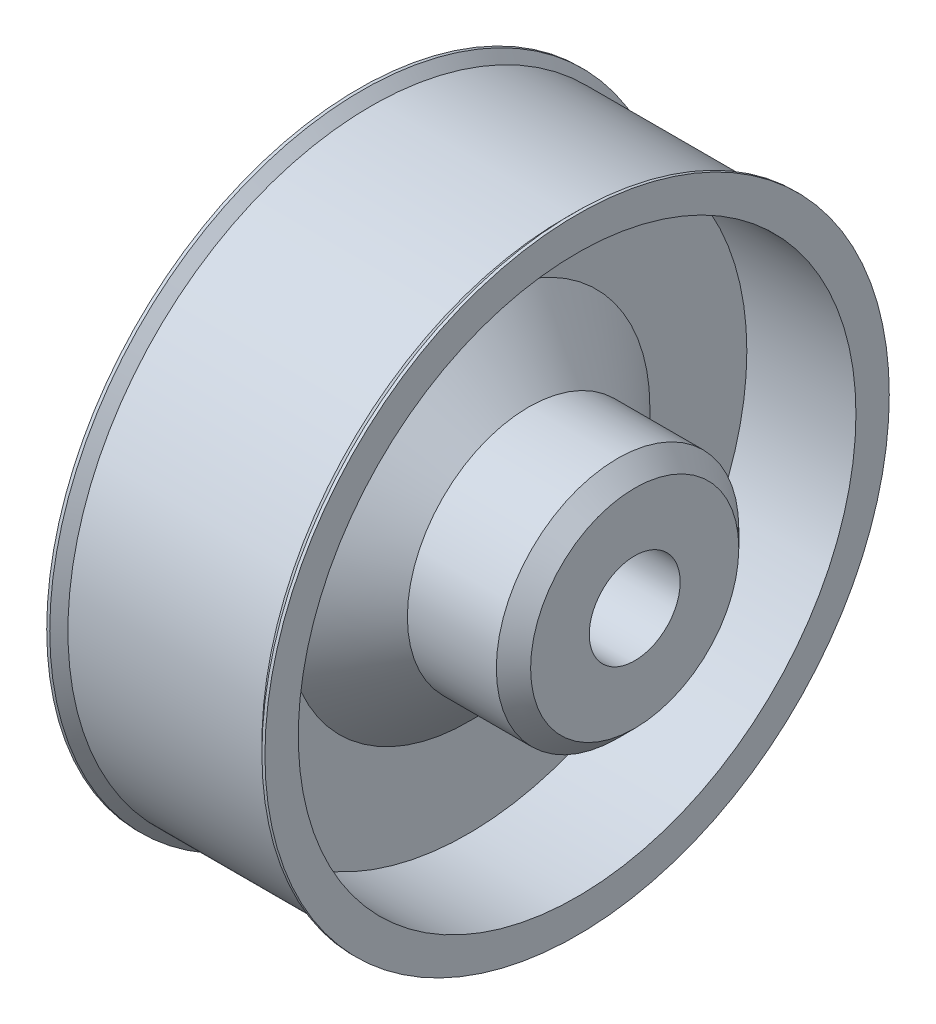
SolidWorks part; units mm, degrees
ref_plane "Ön Düzlem" through (0, 0, 0) normal (0, 0, 1) x (1, 0, 0)
ref_plane "Üst Düzlem" through (0, 0, 0) normal (0, 1, 0) x (1, 0, 0)
ref_plane "Sağ Düzlem" through (0, 0, 0) normal (1, 0, 0) x (0, 0, -1)
sketch "Çizim1" plane through (0, 0, 0) normal (0, 0, 1) x (1, 0, 0)
  line L0 (0, 34.0208) -> (0, 0) construction
  line L1 (0, 0) -> (-25.8271, 0) construction
  line L2 (-7.5, 6) -> (-17.5063, 3.75)
  line L3 (-17.5063, 3.75) -> (-18, 0)
  line L4 (-18, 0) -> (0, 0)
  line L5 (0, 0) -> (0, 7.5)
  line L6 (0, 7.5) -> (27.5, 7.5)
  line L7 (27.5, 7.5) -> (27.5, 17.1716)
  line L8 (27.5, 17.1716) -> (24.6716, 20)
  line L9 (24.6716, 20) -> (10, 20)
  line L10 (10, 20) -> (0, 30)
  line L11 (-7.5, 6) -> (-7.5, 12.9377)
  line L12 (-7.5, 33.0623) -> (-7.5, 43)
  line L13 (0, 30) -> (0, 46)
  line L14 (0, 46) -> (18, 46)
  line L15 (18, 46) -> (18, 51.5)
  line L16 (18, 51.5) -> (17.5, 51.5)
  line L17 (17.5, 51.5) -> (16, 50)
  line L18 (16, 50) -> (-16, 50)
  line L19 (-17.5, 51.5) -> (-16, 50)
  line L20 (-17.5, 51.5) -> (-18, 51.5)
  line L21 (-18, 51.5) -> (-18, 48)
  line L22 (-16, 46) -> (-10.5, 46)
  arc A0 (-9.6429, 15.8126) -> (-9.6429, 30.1874) centre (-7.5, 23) cw
  arc A1 (-7.5, 12.9377) -> (-9.6429, 15.8126) centre (-10.5, 12.9377) ccw
  arc A2 (-9.6429, 30.1874) -> (-7.5, 33.0623) centre (-10.5, 33.0623) ccw
  arc A3 (-7.5, 43) -> (-10.5, 46) centre (-10.5, 43) ccw
  arc A4 (-18, 48) -> (-16, 46) centre (-16, 48) ccw
  point P24 (15.2043, 58.4268)
  point P27 (0, 0)
  point P28 (14.8955, 58.118)
  point P29 (0, 0)
  point P30 (10, 59.3231)
  point P31 (-27.6136, 57.8457)
  point P32 (-25.8271, 54.1976)
  point P33 (-12.2249, 56.4915)
  point P34 (-12.2249, 54.768)
  point P35 (-15.9182, 58.5844)
  point P36 (-17.5063, 51.1536)
  point P37 (-17.5063, 51.6049)
  point P38 (-17.5063, 51.6049)
  point P39 (0, 0)
  point P40 (0, 0)
  point P41 (-15.4152, 46.9148)
  point P42 (0, 0)
  point P43 (0, 0)
  point P44 (0, 0)
  dimension "D7" = 7.5
  dimension "D23" = 3
  dimension "D24" = 2
  dimension "D1" = 18
  dimension "D2" = 82.5
  dimension "D3" = 7.5
  dimension "D4" = 3.75
  dimension "D5" = 6
  dimension "D6" = 23
  dimension "D8" = 7.5
  dimension "D9" = 45.5
  dimension "D10" = 20
  dimension "D11" = 4
  dimension "D12" = 45
  dimension "D13" = 10
  dimension "D14" = 45
  dimension "D15" = 36
  dimension "D16" = 10
  dimension "D17" = 46
  dimension "D18" = 51.5
  dimension "D19" = 0.5
  dimension "D20" = 0.5
  dimension "D21" = 32
  dimension "D22" = 2
revolve "Döndür1" add sketch "Çizim1" angle 360 about L1
sketch "Çizim3" plane through (-7.5, 0, 0) normal (-1, 0, 0) x (0, 0, 1)
  line L0 (0, 0) -> (0, 37.5) construction
  line L2 (2.8868, 37.5) -> (1.4434, 40)
  line L3 (1.4434, 40) -> (-1.4434, 40)
  line L4 (-1.4434, 40) -> (-2.8868, 37.5)
  line L5 (-2.8868, 37.5) -> (-1.4434, 35)
  line L6 (-1.4434, 35) -> (1.4434, 35)
  line L7 (1.4434, 35) -> (2.8868, 37.5)
  circle A0 centre (0, 37.5) radius 2.5 construction
  dimension "D1" = 5
  dimension "D2" = 37.5
extrude "Yükseklik-Ekstrüzyon1" add sketch "Çizim3" along normal blind 3
pattern_circular "Dairesel Kaplama1" count 9 over 360 about axis through (0, 0, 0) along (1, 0, 0) of "Yükseklik-Ekstrüzyon1"
sketch "Çizim5" plane through (-7.5, 0, 0) normal (-1, 0, 0) x (0, 0, 1)
  line L1 (2.8868, 10) -> (1.4434, 12.5)
  line L2 (1.4434, 12.5) -> (-1.4434, 12.5)
  line L3 (-1.4434, 12.5) -> (-2.8868, 10)
  line L4 (-2.8868, 10) -> (-1.4434, 7.5)
  line L5 (-1.4434, 7.5) -> (1.4434, 7.5)
  line L6 (1.4434, 7.5) -> (2.8868, 10)
  circle A0 centre (0, 10) radius 2.5 construction
  dimension "D1" = 5
  dimension "D2" = 10
extrude "Yükseklik-Ekstrüzyon2" add sketch "Çizim5" along normal blind 3
pattern_circular "Dairesel Kaplama2" count 5 over 360 about axis through (0, 0, 0) along (1, 0, 0) of "Yükseklik-Ekstrüzyon2"
